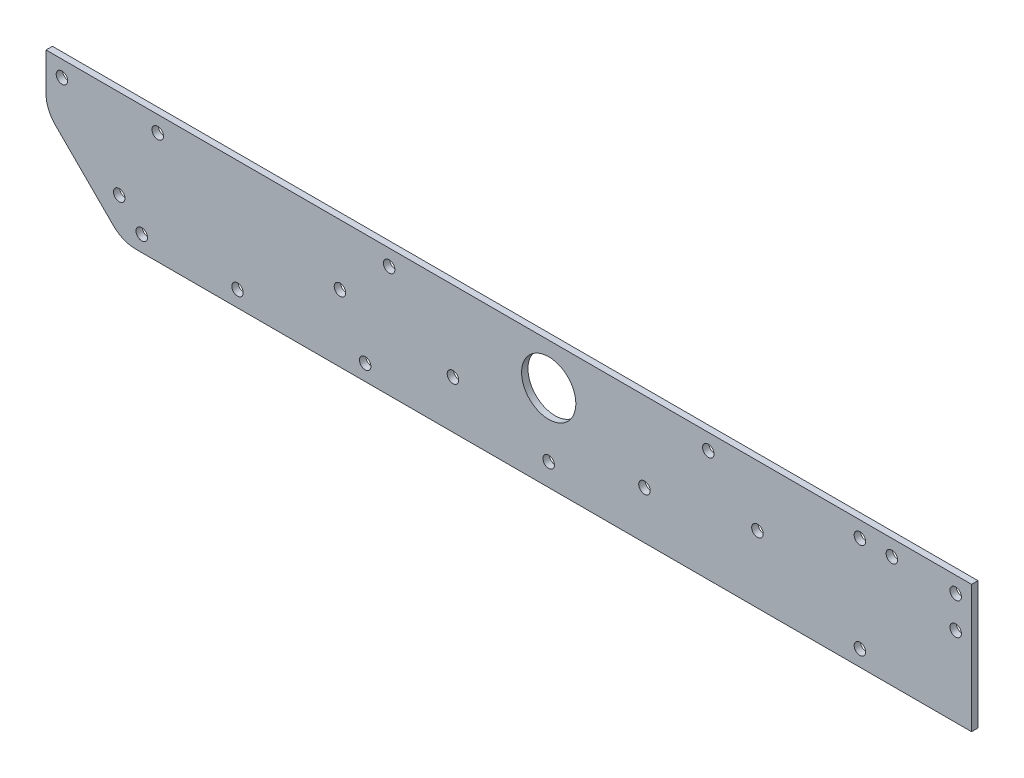
SolidWorks part; units mm, degrees
ref_plane "Front Plane" through (0, 0, 0) normal (0, 0, 1) x (1, 0, 0)
ref_plane "Top Plane" through (0, 0, 0) normal (0, 1, 0) x (1, 0, 0)
ref_plane "Right Plane" through (0, 0, 0) normal (1, 0, 0) x (0, 0, -1)
sketch "Sketch1" plane through (0, 0, 0) normal (0, 0, 1) x (1, 0, 0)
  line L0 (-206.375, 19.05) -> (-130.175, 19.05) construction
  line L1 (0, 0) -> (-368.3, 0)
  line L2 (0, 0) -> (0, 50.8)
  line L3 (0, 50.8) -> (-368.3, 50.8)
  line L4 (-368.3, 0) -> (-368.3, 50.8)
  line L5 (-168.275, 6.35) -> (-168.275, 34.29) construction
  line L6 (-292.1, 6.35) -> (-44.45, 6.35) construction
  line L7 (-251.333, 26.67) -> (-251.333, 6.35) construction
  line L8 (-330.2, 6.35) -> (-339.1803, 15.3303) construction
  circle A0 centre (-44.45, 6.35) radius 2.286
  circle A2 centre (-292.1, 6.35) radius 2.286
  circle A4 centre (-130.175, 19.05) radius 2.286
  circle A5 centre (-206.375, 19.05) radius 2.286
  circle A6 centre (-168.275, 34.29) radius 10.795
  circle A7 centre (-251.333, 26.67) radius 2.286
  circle A8 centre (-85.217, 26.67) radius 2.286
  circle A11 centre (-330.2, 6.35) radius 2.286
  circle A12 centre (-241.3, 6.35) radius 2.286
  circle A13 centre (-361.95, 44.45) radius 2.286
  circle A14 centre (-323.85, 44.45) radius 2.286
  circle A15 centre (-339.1803, 15.3303) radius 2.286
  point P17 (-168.275, 19.05)
  dimension "D3" = 6.35
  dimension "D5" = 4.572
  dimension "D6" = 76.2
  dimension "D9" = 12.7
  dimension "D10" = 21.59
  dimension "D11" = 4.572
  dimension "D1" = 50.8
  dimension "D2" = 368.3
  dimension "D4" = 44.45
  dimension "D7" = 247.65
  dimension "D8" = 27.94
  dimension "D12" = 83.058
  dimension "D13" = 20.32
  dimension "D14" = 38.1
  dimension "D15" = 50.8
  dimension "D16" = 85.725
  dimension "D17" = 6.35
  dimension "D18" = 6.35
  dimension "D19" = 6.35
  dimension "D20" = 38.1
  dimension "D21" = 45
  dimension "D22" = 12.7
extrude "Boss-Extrude1" add sketch "Sketch1" along normal blind 2.54
sketch "Sketch2" plane through (0, 0, 2.54) normal (0, 0, 1) x (1, 0, 0)
  line L0 (-388.62, 50.8) -> (-337.82, 0)
  line L2 (-368.3, 0) -> (0, 0) construction
  line L3 (-388.62, 50.8) -> (-388.62, 0)
  line L4 (-388.62, 0) -> (-337.82, 0)
  line L5 (0, 0) -> (0, 50.8) construction
  line L6 (0, 50.8) -> (-368.3, 50.8) construction
  dimension "D1" = 50.8
  dimension "D2" = 337.82
extrude "Cut-Extrude1" cut sketch "Sketch2" against normal blind 2.54
fillet "Fillet1" radius 12.7 2 edges at (-337.82, 0, 1.27) (-368.3, 30.48, 1.27)
sketch "Sketch3" plane through (0, 0, 2.54) normal (0, 0, 1) x (1, 0, 0)
  line L0 (-257.175, 0) -> (-206.375, 6.35)
  line L1 (-332.5595, 0) -> (0, 0) construction
  line L2 (-206.375, 6.35) -> (-130.175, 6.35)
  line L3 (-130.175, 6.35) -> (-79.375, 0)
  line L4 (-79.375, 0) -> (-257.175, 0)
  point P4 (-130.175, 19.05)
  point P7 (-206.375, 19.05)
  dimension "D1" = 50.8
  dimension "D2" = 50.8
  dimension "D3" = 12.7
extrude "Cut-Extrude2" [suppressed] cut sketch "Sketch3" against normal through all
sketch "Sketch4" plane through (0, 0, 2.54) normal (0, 0, 1) x (1, 0, 0)
  line L0 (-231.775, 44.45) -> (-104.775, 44.45) construction
  line L1 (-168.275, 34.29) -> (-168.275, 8.89) construction
  circle A0 centre (-231.775, 44.45) radius 2.286
  circle A1 centre (-104.775, 44.45) radius 2.286
  circle A2 centre (-168.275, 8.89) radius 2.286
  point P3 (-168.275, 34.29)
  point P12 (-168.275, 44.45)
  dimension "D2" = 25.4
  dimension "D3" = 4.572
  dimension "D1" = 127
  dimension "D4" = 10.16
extrude "Cut-Extrude3" cut sketch "Sketch4" against normal through all
sketch "Sketch5" plane through (0, 0, 2.54) normal (0, 0, 1) x (1, 0, 0)
  line L0 (-44.45, 6.35) -> (-44.45, 44.45) construction
  line L1 (-44.45, 44.45) -> (-31.75, 44.45) construction
  line L2 (0, 0) -> (0, 50.8) construction
  circle A0 centre (-44.45, 44.45) radius 2.286
  circle A1 centre (-31.75, 44.45) radius 2.286
  circle A2 centre (-6.35, 44.45) radius 2.286
  circle A3 centre (-6.35, 31.75) radius 2.286
  dimension "D1" = 4.572
  dimension "D2" = 38.1
  dimension "D3" = 12.7
  dimension "D4" = 6.35
  dimension "D5" = 12.7
extrude "Cut-Extrude4" cut sketch "Sketch5" against normal through all
